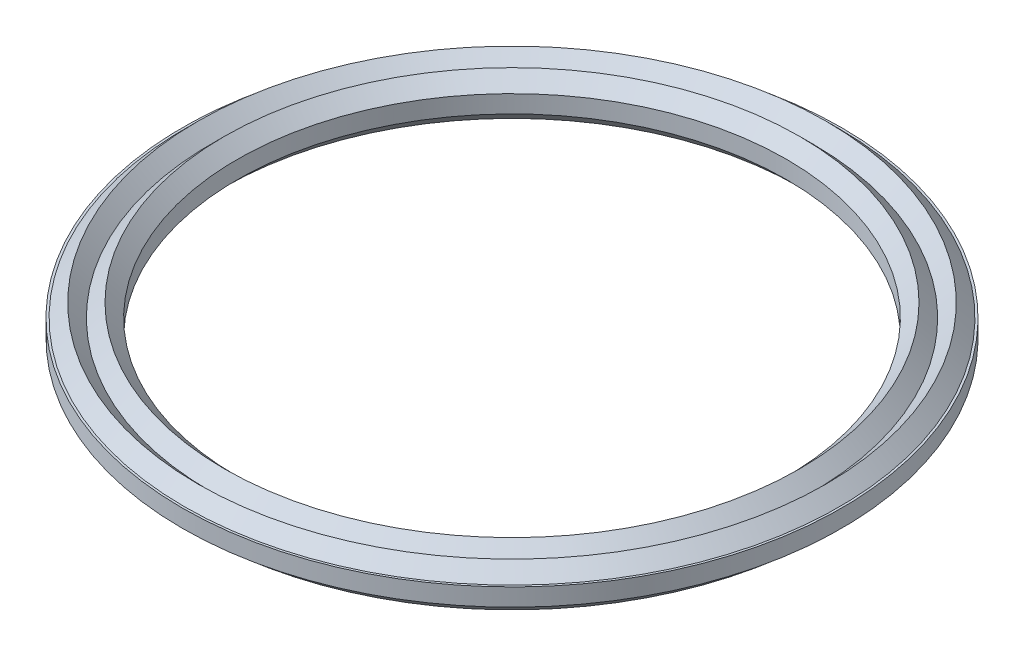
SolidWorks part; units mm, degrees
material "Медь"
ref_plane "Спереди" through (0, 0, 0) normal (0, 0, 1) x (1, 0, 0)
ref_plane "Сверху" through (0, 0, 0) normal (0, 1, 0) x (1, 0, 0)
ref_plane "Справа" through (0, 0, 0) normal (1, 0, 0) x (0, 0, -1)
sketch "Эскиз1" plane through (0, 0, 0) normal (0, 0, 1) x (1, 0, 0)
  line L0 (0, 0) -> (0, 33.0115) construction
  line L1 (12.5, 0.4) -> (12.5, -0.4)
  line L2 (12.5, -0.4) -> (13.1, -1)
  line L3 (13.1, -1) -> (13.7, -0.4)
  line L4 (13.7, -0.4) -> (14.3, -1)
  line L5 (14.3, -1) -> (14.9, -0.4)
  line L6 (14.9, -0.4) -> (15, -0.4)
  line L7 (15, -0.4) -> (15, 0.4)
  line L8 (15, 0.4) -> (14.9, 0.4)
  line L9 (14.9, 0.4) -> (14.3, 1)
  line L10 (14.3, 1) -> (13.7, 0.4)
  line L11 (13.7, 0.4) -> (13.1, 1)
  line L12 (13.1, 1) -> (12.5, 0.4)
  line L13 (15, 0) -> (0, 0) construction
  dimension "D1" = 0.8
  dimension "D2" = 2
  dimension "D3" = 30
  dimension "D4" = 25
  dimension "D5" = 90
revolve "Повернуть1" add sketch "Эскиз1" angle 360 about L0
